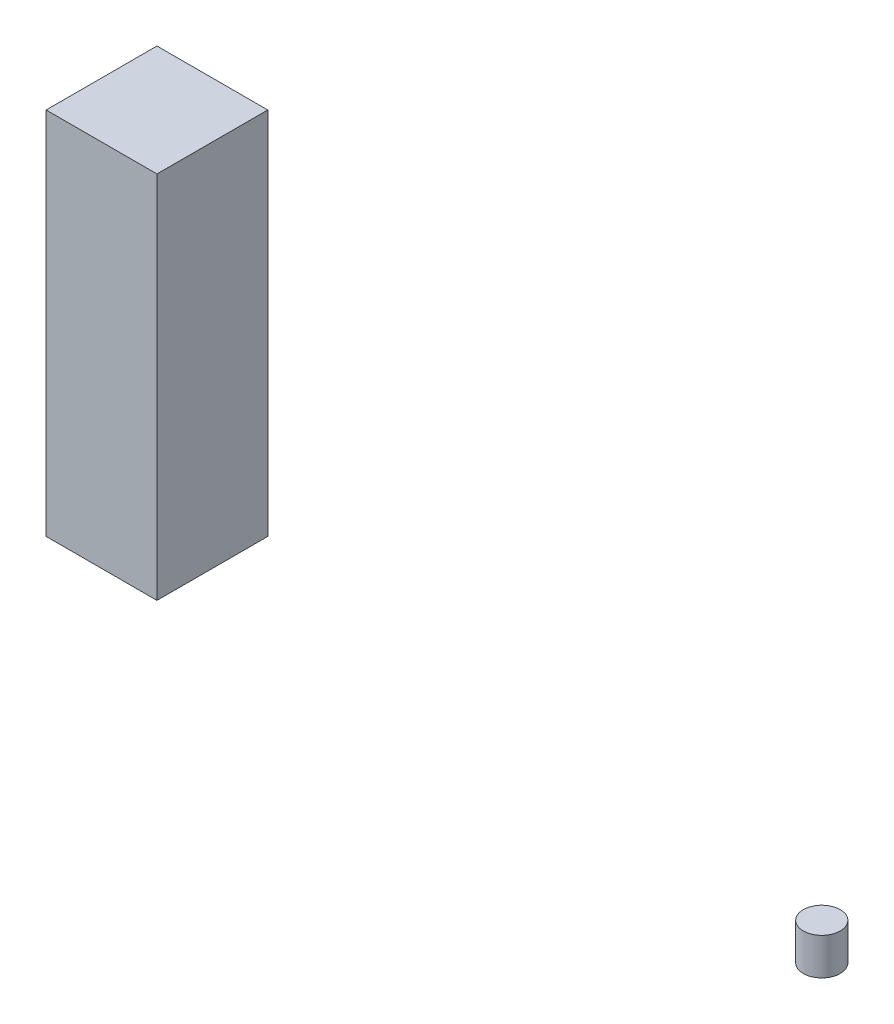
SolidWorks part; units mm, degrees
ref_plane "Front Plane" through (0, 0, 0) normal (0, 0, 1) x (1, 0, 0)
ref_plane "Top Plane" through (0, 0, 0) normal (0, 1, 0) x (1, 0, 0)
ref_plane "Right Plane" through (0, 0, 0) normal (1, 0, 0) x (0, 0, -1)
sketch "Sketch1" plane through (0, 0, 0) normal (0, 1, 0) x (1, 0, 0)
  line L1 (15, -15) -> (-15, -15)
  line L2 (15, -15) -> (15, 15)
  line L3 (15, 15) -> (-15, 15)
  line L4 (-15, -15) -> (-15, 15)
  line L5 (15, -15) -> (-15, 15) construction
  line L6 (15, 15) -> (-15, -15) construction
  point P0 (0, 0)
  dimension "D1" = 30
  dimension "D2" = 30
extrude "Boss-Extrude1" add sketch "Sketch1" along normal blind 100
sketch "Sketch2" plane through (0, 0, 0) normal (0, -1, 0) x (1, 0, 0)
  line L0 (0, 0) -> (89.1733, 0) construction
  line L1 (15, 15) -> (15, -15) construction
  circle A0 centre (180, 0) radius 5
  dimension "D2" = 10
  dimension "D1" = 165
extrude "Boss-Extrude2" add sketch "Sketch2" along normal blind 10 separate body
